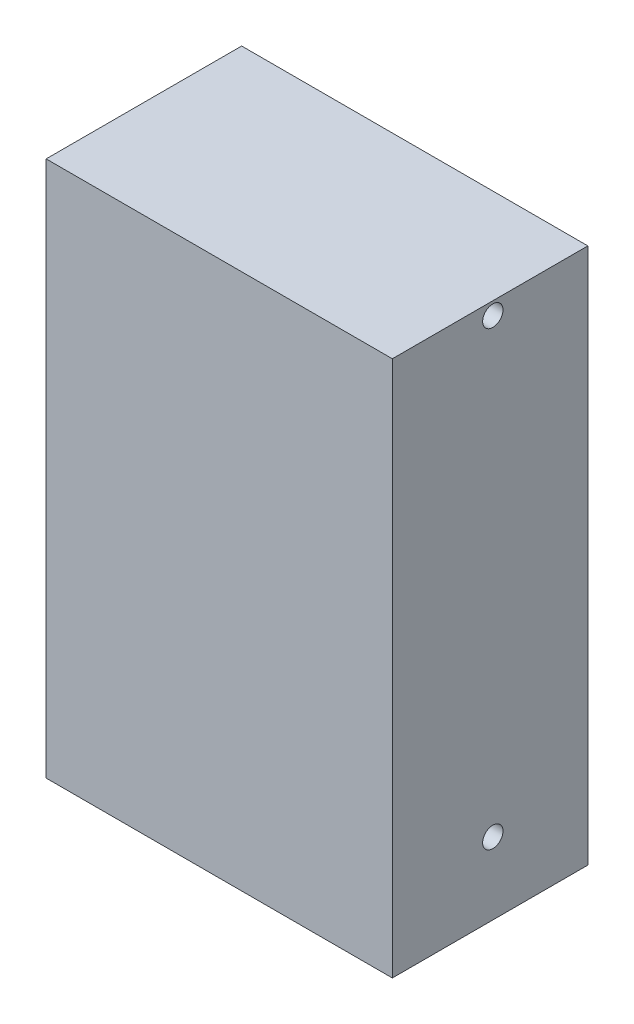
SolidWorks part; units mm, degrees
ref_plane "前视基准面" through (0, 0, 0) normal (0, 0, 1) x (1, 0, 0)
ref_plane "上视基准面" through (0, 0, 0) normal (0, 1, 0) x (1, 0, 0)
ref_plane "右视基准面" through (0, 0, 0) normal (1, 0, 0) x (0, 0, -1)
sketch "草图1" plane through (0, 0, 0) normal (0, 0, 1) x (1, 0, 0)
  line L1 (-25.5, 39.5) -> (25.5, 39.5)
  line L2 (-25.5, 39.5) -> (-25.5, -39.5)
  line L3 (-25.5, -39.5) -> (25.5, -39.5)
  line L4 (25.5, 39.5) -> (25.5, -39.5)
  line L5 (-25.5, 39.5) -> (25.5, -39.5) construction
  line L6 (-25.5, -39.5) -> (25.5, 39.5) construction
  point P0 (0, 0)
  dimension "D1" = 51
  dimension "D2" = 79
extrude "凸台-拉伸1" add sketch "草图1" along normal blind 28.8
sketch "草图2" plane through (0, 0, 0) normal (0, 0, -1) x (-1, 0, 0)
  line L0 (0, 56.8956) -> (0, -58.5173) construction
  line L1 (-25.5, 39.5) -> (25.5, 39.5) construction
  circle A0 centre (0, 29) radius 1.5
  circle A1 centre (0, -26) radius 1.5
  dimension "D1" = 3
  dimension "D2" = 3
  dimension "D3" = 55
  dimension "D4" = 10.5
extrude "切除-拉伸1" cut sketch "草图2" against normal blind 5
sketch "草图3" plane through (25.5, 0, 0) normal (1, 0, 0) x (0, 0, -1)
  line L0 (-14, 88.4253) -> (-14, -49.3325) construction
  line L1 (-28.8, 39.5) -> (0, 39.5) construction
  line L2 (0, -39.5) -> (0, 39.5) construction
  circle A0 centre (-14, 37.6) radius 1.5
  circle A1 centre (-14, -28.9) radius 1.5
  dimension "D1" = 3
  dimension "D2" = 3
  dimension "D3" = 66.5
  dimension "D4" = 1.9
  dimension "D5" = 14
extrude "切除-拉伸2" cut sketch "草图3" against normal blind 5
sketch "草图4" plane through (0, -39.5, 0) normal (0, -1, 0) x (1, 0, 0)
  line L1 (-25.5, 17) -> (15.5, 17)
  line L2 (-25.5, 17) -> (-25.5, 5)
  line L3 (-25.5, 5) -> (15.5, 5)
  line L4 (15.5, 17) -> (15.5, 5)
  line L5 (-25.5, 28.8) -> (-25.5, 0) construction
  line L6 (-25.5, 0) -> (25.5, 0) construction
  dimension "D1" = 41
  dimension "D2" = 12
  dimension "D3" = 5
extrude "切除-拉伸3" cut sketch "草图4" against normal blind 5
